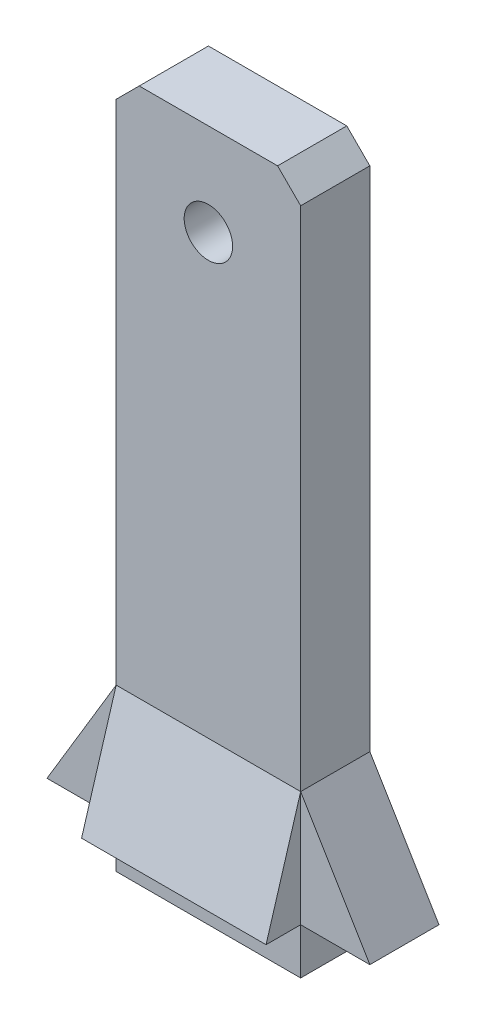
SolidWorks part; units mm, degrees
ref_plane "Front Plane" through (0, 0, 0) normal (0, 0, 1) x (1, 0, 0)
ref_plane "Top Plane" through (0, 0, 0) normal (0, 1, 0) x (1, 0, 0)
ref_plane "Right Plane" through (0, 0, 0) normal (1, 0, 0) x (0, 0, -1)
sketch "Sketch1" plane through (0, 0, 0) normal (0, 1, 0) x (1, 0, 0)
  line L1 (-20, 7.5) -> (20, 7.5)
  line L2 (-20, 7.5) -> (-20, -7.5)
  line L3 (-20, -7.5) -> (20, -7.5)
  line L4 (20, 7.5) -> (20, -7.5)
  line L5 (-20, 7.5) -> (20, -7.5) construction
  line L6 (-20, -7.5) -> (20, 7.5) construction
  point P0 (0, 0)
  dimension "D1" = 40
  dimension "D2" = 15
extrude "Boss-Extrude1" add sketch "Sketch1" along normal blind 150
sketch "Sketch3" plane through (0, 0, 7.5) normal (0, 0, 1) x (1, 0, 0)
  line L0 (-20, 150) -> (20, 150) construction
  line L1 (0, 130) -> (0, 150) construction
  circle A0 centre (0, 130) radius 5.25
  dimension "D1" = 10.5
  dimension "D2" = 20
extrude "Cut-Extrude1" cut sketch "Sketch3" against normal through all
chamfer "Chamfer1" distance 5 angle 45 2 edges at (-20, 150, 0) (20, 150, 0)
sketch "Sketch5" plane through (0, 0, 0) normal (1, 0, 0) x (0, 0, -1)
  line L0 (-7.5, 35) -> (-15, 10)
  line L1 (-7.5, 145) -> (-7.5, 0) construction
  line L2 (-15, 10) -> (-7.5, 10)
  line L3 (-7.5, 10) -> (-7.5, 35)
  line L4 (-7.5, 0) -> (7.5, 0) construction
  dimension "D1" = 10
  dimension "D2" = 7.5
  dimension "D3" = 25
extrude "Boss-Extrude2" add sketch "Sketch5" along normal mid plane 40
sketch "Sketch7" plane through (0, 0, 0) normal (0, 0, 1) x (1, 0, 0)
  line L0 (-20, 35) -> (-35, 10)
  line L1 (-35, 10) -> (-20, 10)
  line L2 (-20, 10) -> (-20, 35)
  line L3 (20, 35) -> (20, 10)
  line L4 (20, 10) -> (35, 10)
  line L5 (35, 10) -> (20, 35)
  line L6 (20, 10) -> (-20, 10) construction
  dimension "D1" = 15
  dimension "D2" = 15
extrude "Boss-Extrude3" add sketch "Sketch7" along normal mid plane 15
sketch "Sketch8" plane through (0, 0, -7.5) normal (0, 0, -1) x (-1, 0, 0)
  line L0 (-20, 83.3632) -> (20, 83.3632) construction
  line L1 (-20, 145) -> (-20, 35) construction
  line L2 (20, 145) -> (20, 35) construction
  text T0 "CAD" font "Times New Roman" height 5
extrude "Cut-Extrude2" cut sketch "Sketch8" against normal blind 1
